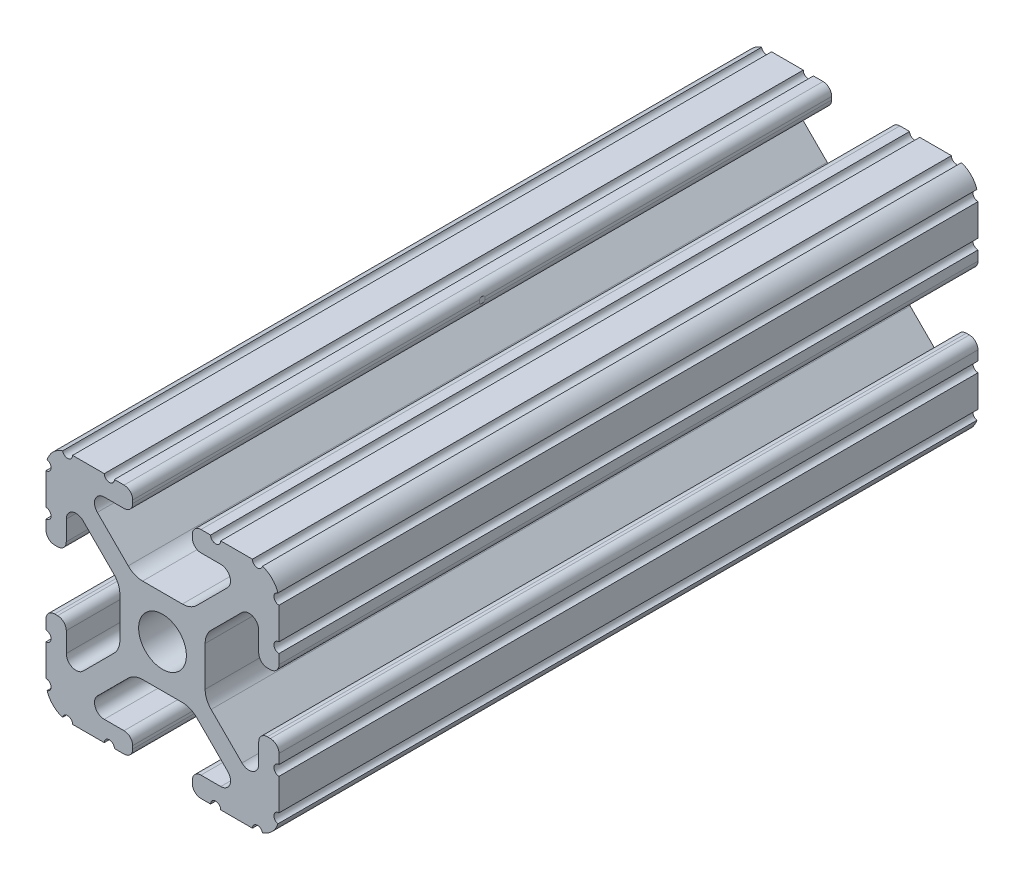
SolidWorks part; units mm, degrees
ref_plane "Front Plane" through (0, 0, 0) normal (0, 0, 1) x (1, 0, 0)
ref_plane "Top Plane" through (0, 0, 0) normal (0, 1, 0) x (1, 0, 0)
ref_plane "Right Plane" through (0, 0, 0) normal (1, 0, 0) x (0, 0, -1)
sketch "Sketch2" plane through (0, 0, 0) normal (0, 0, 1) x (1, 0, 0)
  line L0 (0, 12.7) -> (0, -12.7) construction
  line L1 (-12.7, 0) -> (12.7, 0) construction
  line L2 (3.2512, -12.7) -> (12.7, -12.7)
  line L3 (12.7, -12.7) -> (12.7, -3.2512)
  line L4 (3.2512, -12.7) -> (3.2512, -10.4902)
  line L5 (3.2512, -10.4902) -> (8.9276, -10.4902)
  line L6 (8.9276, -10.4902) -> (3.0856, -4.6482)
  line L7 (0, 0) -> (12.7, -12.7) construction
  line L8 (12.7, -3.2512) -> (10.4902, -3.2512)
  line L9 (10.4902, -3.2512) -> (10.4902, -8.9276)
  line L10 (10.4902, -8.9276) -> (4.6482, -3.0856)
  circle A0 centre (0, 0) radius 2.6035
  arc A1 (6.3485, -10.4902) -> (7.1039, -8.6665) centre (6.3485, -9.4219) ccw construction
  point P8 (0, -4.6482)
  dimension "Center Hole Diameter" = 5.207
  dimension "Rail Height" = 25.4
  dimension "Rail Width" = 25.4
  dimension "T-Slot Width" = 6.5024
  dimension "Slot Inner Width" = 14.8336
  dimension "Thickness" = 2.2098
  dimension "Slot Depth" = 5.842
  dimension "D1" = 2.2098
sketch "Sketch3" plane through (0, 0, 0) normal (1, 0, 0) x (0, 0, -1)
  line L0 (-76.2, -12.7) -> (76.2, -12.7) construction
  line L1 (-68.58, 0) -> (68.58, 0) construction
  dimension "Length" = 152.4
  dimension "D1" = 137.16
sketch "Sketch4" plane through (0, 0, 0) normal (0, 0, 1) x (1, 0, 0)
  line L0 (4.1904, -12.7) -> (10.1173, -12.7)
  line L1 (3.2512, -12.7) -> (12.7, -12.7) construction
  line L2 (3.2512, -12.7) -> (3.2512, -10.4902) construction
  line L3 (3.2512, -10.4902) -> (8.9276, -10.4902) construction
  line L4 (3.2512, -11.4294) -> (3.2512, -11.7608)
  line L5 (4.1904, -10.4902) -> (6.3485, -10.4902)
  line L6 (0, -4.6482) -> (2.164, -4.6482)
  line L7 (8.9276, -10.4902) -> (3.0856, -4.6482) construction
  line L8 (3.7373, -5.2999) -> (7.1039, -8.6665)
  line L9 (12.7, -12.7) -> (12.7, -3.2512) construction
  line L10 (10.4902, -8.9276) -> (4.6482, -3.0856) construction
  line L11 (10.4902, -3.2512) -> (10.4902, -8.9276) construction
  line L12 (10.4902, -6.3485) -> (10.4902, -4.1904)
  line L13 (12.7, -3.2512) -> (10.4902, -3.2512) construction
  line L14 (11.4294, -3.2512) -> (11.7608, -3.2512)
  line L15 (12.7, -4.1904) -> (12.7, -10.1173)
  line L16 (8.6665, -7.1039) -> (5.2999, -3.7373)
  line L17 (4.6482, 0) -> (4.6482, -2.164)
  line L18 (-12.7, 0) -> (12.7, 0) construction
  line L19 (0, -4.6482) -> (0, -2.6035)
  line L20 (0, 12.7) -> (0, -12.7) construction
  line L21 (4.6482, 0) -> (2.6035, 0)
  arc A0 (3.2512, -11.7608) -> (4.1904, -12.7) centre (4.1904, -11.7608) ccw
  arc A2 (3.2512, -11.4294) -> (4.1904, -10.4902) centre (4.1904, -11.4294) cw
  arc A3 (6.3485, -10.4902) -> (7.1039, -8.6665) centre (6.3485, -9.4219) ccw
  arc A4 (2.164, -4.6482) -> (3.7373, -5.2999) centre (2.164, -6.8732) cw
  arc A5 (10.1173, -12.7) -> (12.7, -10.1173) centre (10.1173, -10.1173) ccw
  arc A6 (8.6665, -7.1039) -> (10.4902, -6.3485) centre (9.4219, -6.3485) ccw
  arc A7 (10.4902, -4.1904) -> (11.4294, -3.2512) centre (11.4294, -4.1904) cw
  arc A8 (11.7608, -3.2512) -> (12.7, -4.1904) centre (11.7608, -4.1904) cw
  arc A9 (5.2999, -3.7373) -> (4.6482, -2.164) centre (6.8732, -2.164) cw
  circle A10 centre (0, 0) radius 2.6035 construction
  arc A11 (0, -2.6035) -> (2.6035, 0) centre (0, 0) ccw
  dimension "D1" = 2.5827
  dimension "D2" = 2.225
  dimension "D3" = 0.9392
extrude "Boss-Extrude1" add sketch "Sketch4" along normal mid plane 152.4
sketch "Sketch5" plane through (0, 0, 0) normal (0, 0, 1) x (1, 0, 0)
  line L0 (3.2512, -12.7) -> (12.7, -12.7) construction
  line L1 (4.1904, -10.4902) -> (6.3485, -10.4902) construction
  line L3 (0, 0) -> (12.7, -12.7) construction
  line L4 (6.3485, -10.4902) -> (6.3485, -12.7) construction
  line L5 (8.9276, -10.4902) -> (3.0856, -4.6482) construction
  circle A0 centre (10.3562, -12.7) radius 0.5524
  circle A1 centre (5.796, -12.7) radius 0.5524
  circle A2 centre (12.7, -10.3562) radius 0.5524
  circle A3 centre (12.7, -5.796) radius 0.5524
  point P10 (5.2694, -10.4902)
  point P12 (9.4219, -6.3485)
  dimension "D1" = 1.1049
extrude "Cut-Extrude1" cut sketch "Sketch5" against normal through all both and the other way through all
mirror "Mirror1" about plane through (0, 0, 0) normal (1, 0, 0) of bodies 137 134
mirror "Mirror2" about plane through (0, 0, 0) normal (0, 1, 0) of bodies 135
ref_plane "Plane1" through (0, 0, 0) normal (0, 0, -1) x (-1, 0, 0)
sketch "Sketch6" plane through (0, 0, 0) normal (0, 0, -1) x (-1, 0, 0)
  line L0 (-12.7, 9.8037) -> (-12.7, 6.3485) construction
  line L1 (-12.7, 12.7) -> (12.7, 12.7)
  line L2 (-12.7, 12.7) -> (-12.7, -12.7)
  line L3 (-12.7, -12.7) -> (12.7, -12.7)
  line L4 (12.7, 12.7) -> (12.7, -12.7)
  line L5 (12.7, 9.8037) -> (12.7, 6.3485) construction
  line L6 (-6.3485, 12.7) -> (-9.8037, 12.7) construction
  line L7 (-6.3485, -12.7) -> (-9.8037, -12.7) construction
extrude "Cut-Extrude4" cut sketch "Sketch6" against normal through all
sketch "Sketch7" plane through (0, 12.7, 0) normal (0, 1, 0) x (1, 0, 0)
  line L0 (-12.58, 0) -> (12.7, 0) construction
  line L1 (12.7, 0) -> (-12.7, 0) construction
  line L2 (0, 0) -> (0, -12.7) construction
  circle A0 centre (0, 6.35) radius 3.2639
  dimension "D2" = 6.5278
  dimension "D3" = 19.05
sketch "Sketch8" plane through (0, 12.7, 0) normal (0, 1, 0) x (1, 0, 0)
  line L0 (0, 0) -> (0, 76.2) construction
  line L1 (-2.164, 76.2) -> (2.164, 76.2) construction
  circle A0 centre (0, 38.1) radius 3.2639
  dimension "D1" = 6.5278
extrude "Cut-Extrude6" cut sketch "Sketch8" against normal through all contours A0
sketch "Sketch9" plane through (12.7, 0, 0) normal (1, 0, 0) x (0, 0, -1)
  line L0 (0, 0) -> (12.7, 0) construction
  circle A0 centre (12.7, 0) radius 3.2639
  dimension "D1" = 6.5278
  dimension "D2" = 12.7
equation "\"D1@Boss-Extrude1\"=\"Length@Sketch3\""
equation "\"D1@Sketch2\"=\"Thickness@Sketch2\""
equation "\"D2@Sketch4\"=\"Slot Inner Width@Sketch2\"*0.15"
equation "\"D1@Sketch4\"=\"D3@Sketch4\"*2.75"
equation "\"D3@Sketch4\"=\"Thickness@Sketch2\"*0.425"
equation "\"D1@Sketch5\"=\"Thickness@Sketch2\"*0.5"
equation "\"D1@Sketch3\"=\"Length@Sketch3\"*0.9"
equation "\"D3@Sketch7\"=1.5/2"
